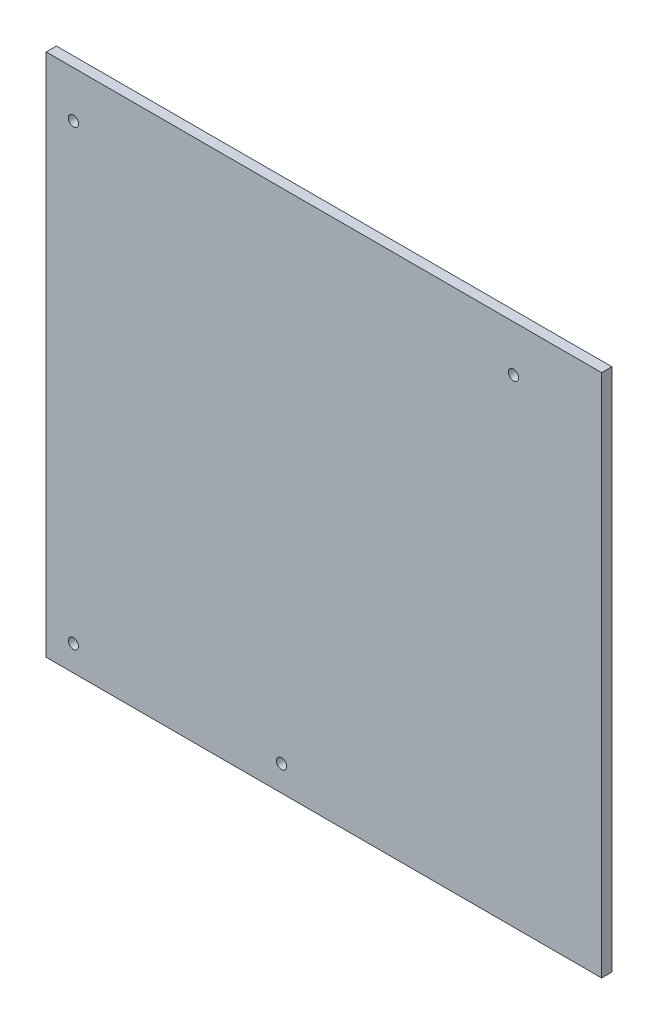
SolidWorks part; units mm, degrees
ref_plane "Front Plane" through (0, 0, 0) normal (0, 0, 1) x (1, 0, 0)
ref_plane "Top Plane" through (0, 0, 0) normal (0, 1, 0) x (1, 0, 0)
ref_plane "Right Plane" through (0, 0, 0) normal (1, 0, 0) x (0, 0, -1)
sketch "Sketch1" plane through (0, 0, 0) normal (0, 0, 1) x (1, 0, 0)
  line L1 (0, 0) -> (162.83, 0)
  line L2 (0, 0) -> (0, 153.6666)
  line L3 (0, 153.6666) -> (162.83, 153.6666)
  line L4 (162.83, 0) -> (162.83, 153.6666)
  circle A0 centre (8, 140.1666) radius 1.5
  circle A1 centre (137, 140.1666) radius 1.5
  circle A2 centre (8, 7.5) radius 1.5
  circle A3 centre (69, 7.5) radius 1.5
  point P13 (0, 0)
  point P14 (0, 0)
  point P15 (0, 0)
  dimension "D3" = 3
  dimension "D4" = 3
  dimension "D12" = 3
  dimension "D13" = 3
  dimension "D1" = 162.83
  dimension "D2" = 153.6666
  dimension "D5" = 8
  dimension "D6" = 13.5
  dimension "D7" = 129
  dimension "D9" = 61
  dimension "D10" = 7.5
  dimension "D11" = 8
extrude "Boss-Extrude1" add sketch "Sketch1" along normal blind 3
